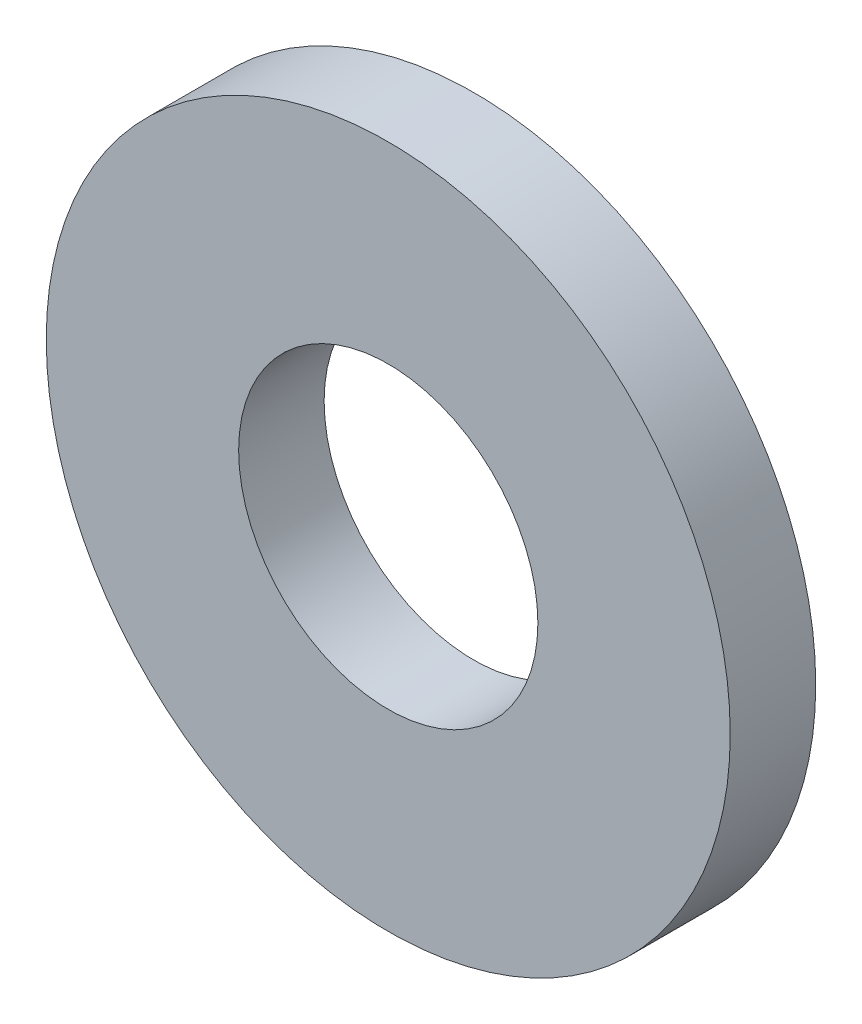
SolidWorks part; units mm, degrees
ref_plane "Front Plane" through (0, 0, 0) normal (0, 0, 1) x (1, 0, 0)
ref_plane "Top Plane" through (0, 0, 0) normal (0, 1, 0) x (1, 0, 0)
ref_plane "Right Plane" through (0, 0, 0) normal (1, 0, 0) x (0, 0, -1)
sketch "Sketch1" plane through (0, 0, 0) normal (0, 0, 1) x (1, 0, 0)
  circle A0 centre (0, 0) radius 4
  circle A1 centre (0, 0) radius 1.75
  dimension "D1" = 8
  dimension "D2" = 3.5
extrude "Boss-Extrude1" add sketch "Sketch1" along normal blind 1
